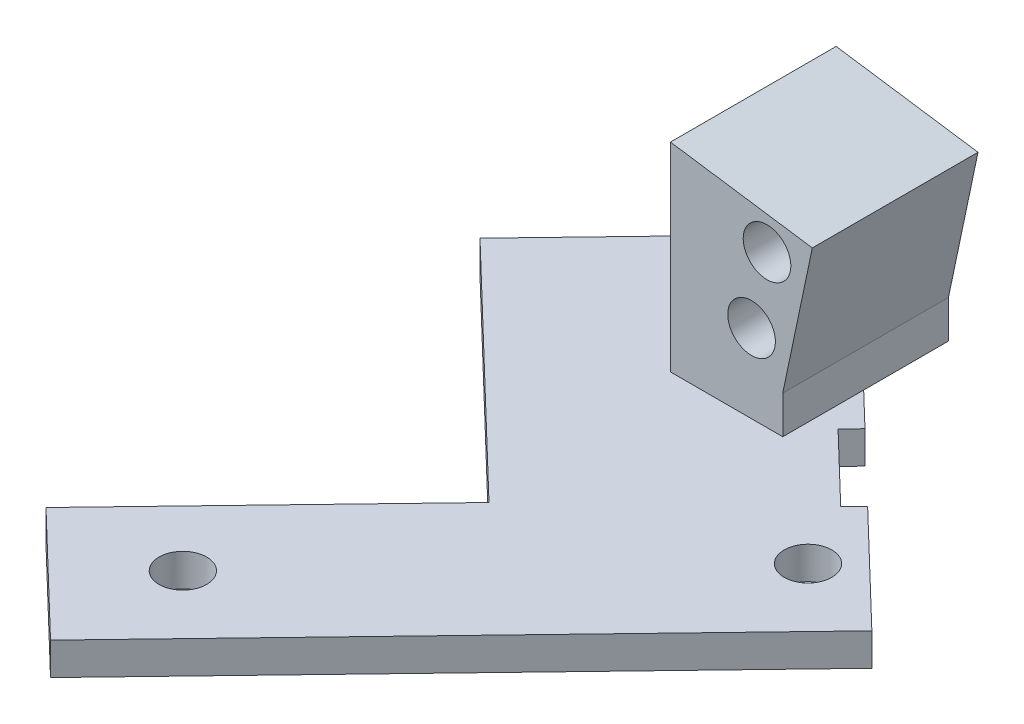
SolidWorks part; units mm, degrees
ref_plane "Front Plane" through (0, 0, 0) normal (0, 0, 1) x (1, 0, 0)
ref_plane "Top Plane" through (0, 0, 0) normal (0, 1, 0) x (1, 0, 0)
ref_plane "Right Plane" through (0, 0, 0) normal (1, 0, 0) x (0, 0, -1)
sketch "Sketch1" plane through (0, 0, 0) normal (0, 0, 1) x (1, 0, 0)
  line L0 (-629.0113, 228.5148) -> (-646.4173, 232.1744)
  line L1 (-625.5069, 227.7779) -> (-640.2031, 230.8679) construction
  line L2 (-646.4173, 232.1744) -> (-650.3578, 213.4325)
  line L3 (-650.3578, 213.4325) -> (-632.9518, 209.7729)
  line L4 (-626.0822, 208.3286) -> (-644.038, 212.1038) construction
  line L5 (-632.9518, 209.7729) -> (-629.0113, 228.5148)
  circle A0 centre (-635.0536, 225) radius 3.175
  circle A1 centre (-637.1112, 215.214) radius 3.175
  dimension "D4" = 6.35
  dimension "D5" = 6.35
  dimension "D1" = 6.35
  dimension "D2" = 19.1516
  dimension "D3" = 17.7865
extrude "Boss-Extrude1" add sketch "Sketch1" along normal up to surface (22.098 mm away)
sketch "Sketch2" plane through (15.4424, 73.4471, 0) normal (-0.2058, -0.9786, 0) x (0.9786, -0.2058, 0)
  line L0 (-680.3571, 22.098) -> (-680.3571, 0)
  line L1 (-680.3571, 0) -> (-673.9925, 0)
  line L2 (-680.3571, 0) -> (-662.5706, 0) construction
  line L3 (-673.9925, 0) -> (-673.9925, 22.098)
  line L4 (-662.5706, 22.098) -> (-680.3571, 22.098) construction
  line L5 (-673.9925, 22.098) -> (-680.3571, 22.098)
  dimension "D1" = 6.3646
extrude "Boss-Extrude2" add sketch "Sketch2" along normal blind 8.89 contours L5 L0 L1 L3
ref_plane "Plane5" through (0, 204.7328, 0) normal (0, 1, 0) x (1, 0, 0)
sketch "Sketch12" plane through (0, 204.7328, 0) normal (0, 1, 0) x (1, 0, 0)
  line L4 (-673.9093, -79.3977) -> (-658.2914, -94.4137)
  line L5 (-651.3433, 6.3746) -> (-676.0774, -19.351)
  line L6 (-904.3151, 142.1279) -> (780.195, -1477.4584) construction
  line L7 (-658.2914, -94.4137) -> (-604.5985, -38.5685)
  line L8 (-604.5985, -38.5685) -> (-651.3433, 6.3746)
  line L9 (-676.0774, -19.351) -> (-644.9506, -49.2781)
  line L10 (-644.9506, -49.2781) -> (-673.9093, -79.3977)
  circle A0 centre (-657.4844, -77.5717) radius 3.175
  circle A1 centre (-616.6175, -35.0666) radius 3.175
  dimension "D5" = 43.18
  dimension "D7" = 6.35
  dimension "D10" = 6.35
  dimension "D2" = 35.6873
  dimension "D3" = 77.47
  dimension "D4" = 90
  dimension "D6" = 3.81
  dimension "D8" = 45.72
extrude "Boss-Extrude6" add sketch "Sketch12" against normal up to surface (4.3268 mm away)
sketch "Sketch19" plane through (0, 0, 22.098) normal (0, 0, 1) x (1, 0, 0)
  line L0 (-646.4173, 232.1744) -> (-654.0373, 232.1744)
  line L1 (-654.0373, 232.1744) -> (-654.0373, 204.7328)
  line L2 (-673.9093, 204.7328) -> (-658.2914, 204.7328) construction
  line L3 (-654.0373, 204.7328) -> (-652.1869, 204.7328)
  line L4 (-652.1869, 204.7328) -> (-646.4173, 232.1744)
  dimension "D1" = 7.62
extrude "Boss-Extrude12" add sketch "Sketch19" against normal up to surface (22.098 mm away) up to face at (-641.73, 215.3418, 0)
sketch "Sketch20" plane through (0, 0, 0) normal (0, 0, -1) x (-1, 0, 0)
  line L0 (629.0113, 228.5148) -> (654.0373, 232.1744)
  line L1 (654.0373, 232.1744) -> (646.4173, 232.1744)
  line L2 (646.4173, 232.1744) -> (629.0113, 228.5148)
extrude "Cut-Extrude1" cut sketch "Sketch20" against normal blind 35.052
sketch "Sketch21" plane through (0, 0, 0) normal (0, 0, -1) x (-1, 0, 0)
  line L0 (644.1294, 212.123) -> (644.1294, 204.7328)
  line L1 (419.4444, 204.7328) -> (-419.4444, 204.7328) construction
  line L2 (644.1294, 204.7328) -> (645.6832, 204.7328)
  line L3 (645.6832, 204.7328) -> (644.1294, 212.123) construction
  line L4 (645.6832, 204.7328) -> (644.1294, 212.123)
extrude "Boss-Extrude13" add sketch "Sketch21" against normal blind 22.098
sketch "Sketch22" plane through (0, 204.7328, 0) normal (0, 1, 0) x (1, 0, 0)
  line L4 (-644.1294, 0) -> (-644.1294, -22.098)
  line L5 (-632.9518, 0) -> (-644.1294, 0)
  line L6 (-632.9518, -22.098) -> (-632.9518, 0)
  line L7 (-644.1294, -22.098) -> (-632.9518, -22.098)
  line L8 (-644.1294, 0) -> (-644.1294, -22.098)
  line L9 (-632.9518, 0) -> (-644.1294, 0)
  line L10 (-632.9518, -22.098) -> (-632.9518, 0)
  line L11 (-644.1294, -22.098) -> (-632.9518, -22.098)
  dimension "D1" = 0
extrude "Boss-Extrude14" add sketch "Sketch22" along normal up to body
sketch "Sketch23" plane through (0, 0, 22.098) normal (0, 0, 1) x (1, 0, 0)
  line L0 (-647.9291, 231.2812) -> (-647.9291, 204.7328)
  line L1 (-629.0113, 228.5148) -> (-654.0373, 232.1744) construction
  line L2 (-654.0373, 204.7328) -> (-632.9518, 204.7328) construction
  line L3 (-647.9291, 204.7328) -> (-654.0373, 204.7328)
  line L4 (-654.0373, 204.7328) -> (-654.0373, 232.1744)
  line L5 (-654.0373, 232.1744) -> (-654.0373, 204.7328) construction
  line L6 (-654.0373, 232.1744) -> (-647.9291, 231.2812)
extrude "Cut-Extrude3" cut sketch "Sketch23" against normal blind 39.878
sketch "Sketch24" plane through (0, 204.7328, 0) normal (0, 1, 0) x (1, 0, 0)
  line L0 (-619.2465, -24.4852) -> (-621.0069, -26.3161)
  line L1 (-604.5985, -38.5685) -> (-632.9518, -11.308) construction
  line L2 (-621.0069, -26.3161) -> (-630.1618, -17.5141)
  line L3 (-630.1618, -17.5141) -> (-628.4014, -15.6831)
  line L4 (-628.4014, -15.6831) -> (-619.2465, -24.4852)
  line L5 (-658.2914, -94.4137) -> (-604.5985, -38.5685) construction
  dimension "D1" = 12.7
  dimension "D2" = 2.54
  dimension "D3" = 20.32
extrude "Cut-Extrude4" cut sketch "Sketch24" against normal through all
